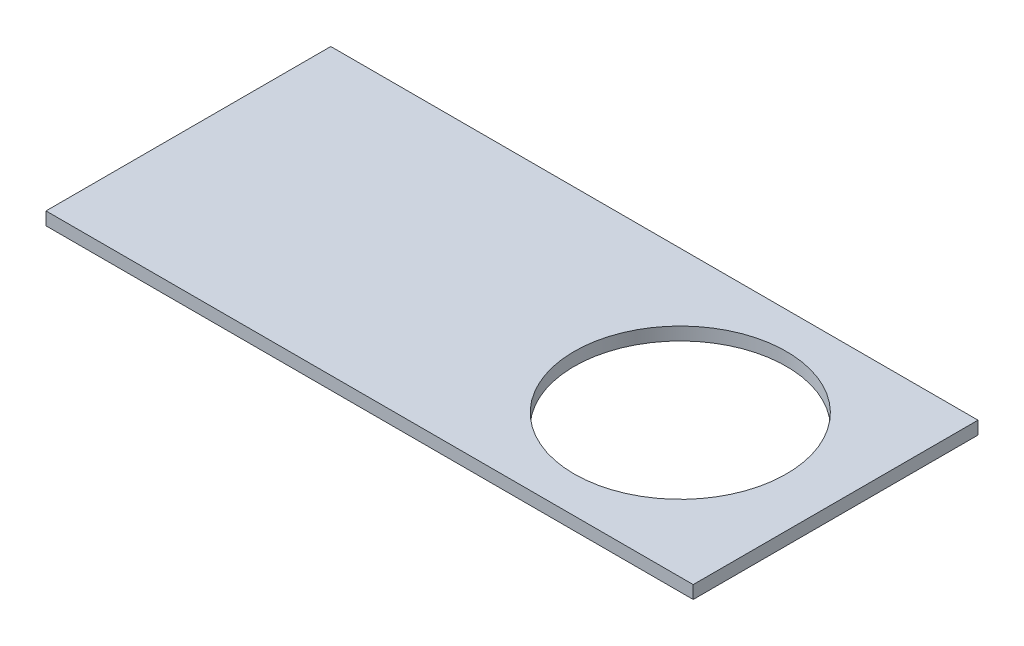
SolidWorks part; units mm, degrees
material "Сталь 3 ГОСТ 535-88"
ref_plane "Спереди" through (0, 0, 0) normal (0, 0, 1) x (1, 0, 0)
ref_plane "Сверху" through (0, 0, 0) normal (0, 1, 0) x (1, 0, 0)
ref_plane "Справа" through (0, 0, 0) normal (1, 0, 0) x (0, 0, -1)
sketch "Эскиз1" plane through (0, 0, 0) normal (0, 1, 0) x (1, 0, 0)
  line L1 (-125, -55) -> (125, -55)
  line L2 (-125, -55) -> (-125, 55)
  line L3 (-125, 55) -> (125, 55)
  line L4 (125, -55) -> (125, 55)
  line L5 (0, 55) -> (0, -55) construction
  line L6 (-125, 0) -> (125, 0) construction
  circle A0 centre (65, 0) radius 41
  point P0 (0, 0)
  dimension "D3" = 82
  dimension "D1" = 250
  dimension "D2" = 110
  dimension "D4" = 60
extrude "Бобышка-Вытянуть1" add sketch "Эскиз1" along normal blind 5
sketch "Эскиз2" [suppressed] plane through (0, 5, 0) normal (0, 1, 0) x (1, 0, 0)
  circle A0 centre (-105, -48.5) radius 3 construction
  circle A1 centre (-105, 48.5) radius 3 construction
  circle A2 centre (105, 48.5) radius 3 construction
  circle A3 centre (105, -48.5) radius 3 construction
  circle A4 centre (-105, -48.5) radius 3
  circle A5 centre (-105, 48.5) radius 3
  circle A6 centre (105, 48.5) radius 3
  circle A7 centre (105, -48.5) radius 3
extrude "Вырез-Вытянуть1" [suppressed] cut sketch "Эскиз2" against normal through all
chamfer "Фаска1" [suppressed] distance 2 angle 45
